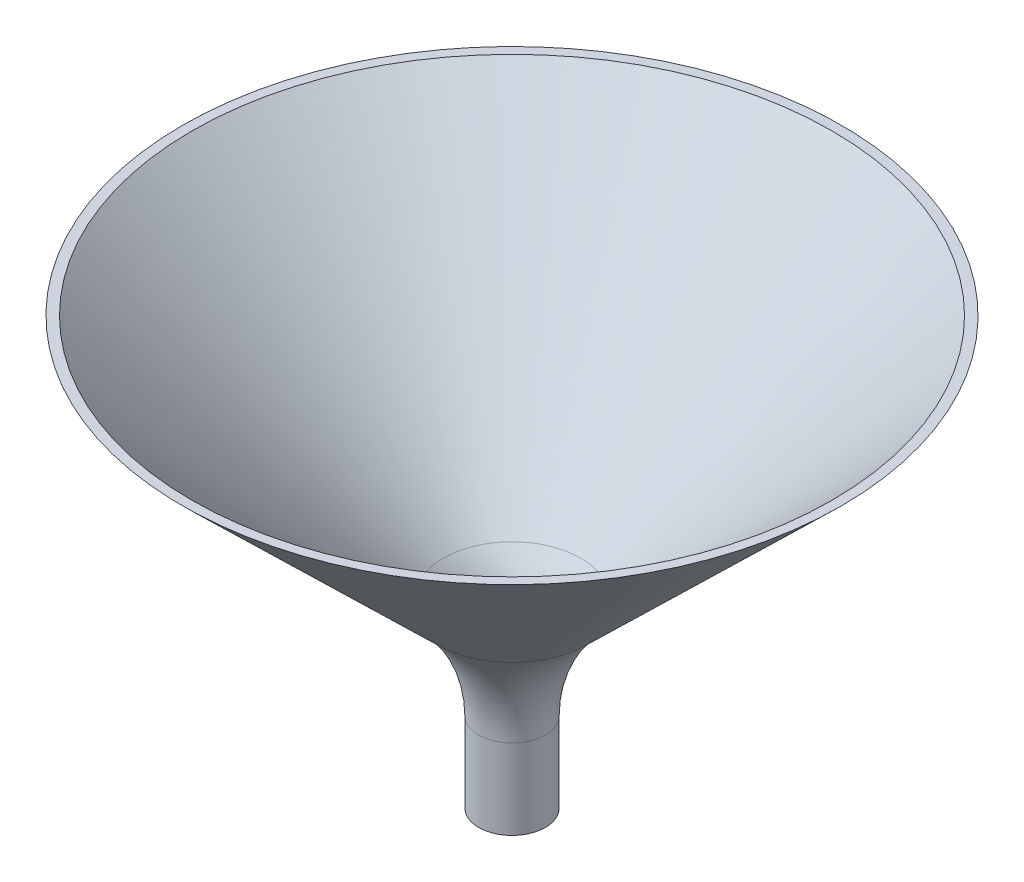
SolidWorks part; units mm, degrees
ref_plane "Front" through (0, 0, 0) normal (0, 0, 1) x (1, 0, 0)
ref_plane "Top" through (0, 0, 0) normal (0, 1, 0) x (1, 0, 0)
ref_plane "Right" through (0, 0, 0) normal (1, 0, 0) x (0, 0, -1)
sketch "Esquisse1" plane through (0, 0, 0) normal (0, 0, 1) x (1, 0, 0)
  line L1 (3.9688, 0) -> (3.9688, 9.5347)
  line L2 (8.97, 21.3723) -> (39.2387, 50.8)
  line L3 (39.2387, 50.8) -> (38.1, 50.8)
  line L4 (38.1, 50.8) -> (8.1763, 21.7077)
  line L5 (3.175, 9.87) -> (3.175, 0)
  line L8 (0, 0) -> (0, 63.5) construction
  line L10 (3.175, 0) -> (3.9688, 0)
  line L11 (0, 0) -> (13.1093, 0) construction
  arc A0 (8.1763, 21.7077) -> (3.175, 9.87) centre (19.685, 9.87) ccw
  arc A1 (3.9688, 9.5347) -> (8.97, 21.3723) centre (20.4788, 9.5347) cw
  point P9 (3.5719, 0)
  point P15 (3.9688, 16.51)
  dimension "D6" = 16.51
  dimension "D1" = 3.175
  dimension "D2" = 50.8
  dimension "D3" = 0.7937
  dimension "D4" = 0.7937
  dimension "D5" = 38.1
  dimension "D7" = 16.51
revolve "Révolution1" add sketch "Esquisse1" angle 360 about L8
sketch "Esquisse2" plane through (0, 0, 0) normal (0, 0, 1) x (1, 0, 0)
  line L7 (0, 0) -> (0, 50.8) construction
  line L8 (39.2387, 50.8) -> (-39.2387, 50.8) construction
  line L9 (39.2387, 50.8) -> (47.3667, 50.8)
  line L10 (47.3667, 50.8) -> (47.3667, 47.625)
  line L11 (47.3667, 47.625) -> (35.973, 47.625)
  line L12 (8.97, 21.3723) -> (39.2387, 50.8) construction
  line L13 (35.973, 47.625) -> (39.2387, 50.8)
  dimension "D1" = 3.175
  dimension "D2" = 8.128
revolve "Révolution2" [suppressed] add sketch "Esquisse2" angle 360 about L7
sketch "Esquisse3" [suppressed] plane through (0, 50.8, 0) normal (0, 1, 0) x (1, 0, 0)
  circle A0 centre (0, 0) radius 42.7947 construction
  circle A1 centre (0, 0) radius 47.3667 construction
  circle A2 centre (0, -42.7947) radius 2.15
  circle A3 centre (-42.5364, -4.6947) radius 2.15
  circle A4 centre (42.5364, -4.6947) radius 2.15
  dimension "D1" = 4.572
  dimension "D2" = 4.3
  dimension "D3" = 38.1
extrude "Enlèv. mat.-Extru.1" [suppressed] cut sketch "Esquisse3" against normal through all
sketch "Esquisse4" plane through (0, 0, 0) normal (0, -1, 0) x (1, 0, 0)
  line L1 (-0.6, 3.9231) -> (0.6, 3.9231)
  line L2 (-0.6, 3.9231) -> (-0.6, -3.9231)
  line L3 (-0.6, -3.9231) -> (0.6, -3.9231)
  line L4 (0.6, 3.9231) -> (0.6, -3.9231)
  circle A0 centre (0, 0) radius 3.9688 construction
  dimension "D1" = 1.2
extrude "Boss.-Extru.1" add sketch "Esquisse4" against normal blind 6.35
